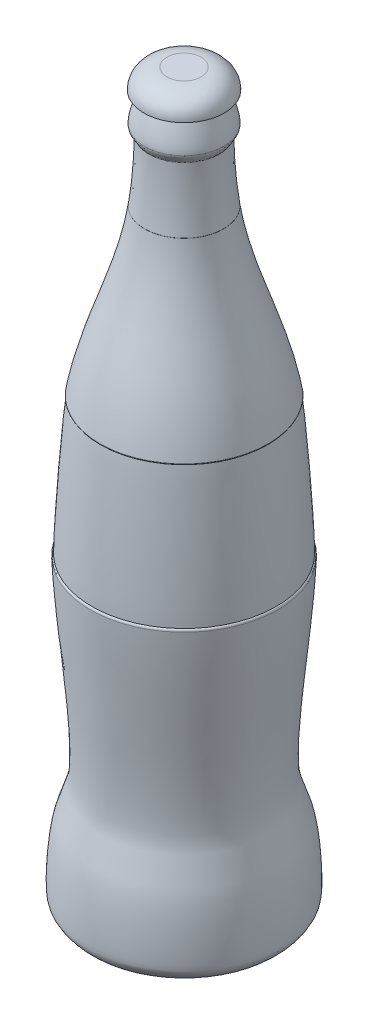
SolidWorks part; units mm, degrees
ref_plane "Plano frontal" through (0, 0, 0) normal (0, 0, 1) x (1, 0, 0)
ref_plane "Plano superior" through (0, 0, 0) normal (0, 1, 0) x (1, 0, 0)
ref_plane "Plano direito" through (0, 0, 0) normal (1, 0, 0) x (0, 0, -1)
sketch "Esboço1" plane through (0, 0, 0) normal (0, 0, 1) x (1, 0, 0)
  line L0 (46.2661, 215.0263) -> (246.2661, 215.0263) construction
  line L1 (103.0084, 498.8129) -> (276.3418, 498.8129) construction
sketch "Esboço2" plane through (0, 0, 0) normal (0, 0, 1) x (1, 0, 0)
  line L0 (0, 0) -> (0, 80) construction
  line L1 (-10, 80) -> (10, 80)
  line L2 (-10, 80) -> (-10, 0)
  line L3 (-10, 0) -> (10, 0)
  line L4 (10, 80) -> (10, 0)
  dimension "D1" = 20
  dimension "D2" = 80
sketch "Esboço3" plane through (0, 0, 0) normal (0, 0, 1) x (1, 0, 0)
  line L0 (69.3939, 0.7286) -> (71.7278, 0.7286) construction
  line L4 (66.4764, 70.3449) -> (66.4764, 74.4591) construction
  line L5 (61.2461, 48.1703) -> (61.269, 48.2958) construction
  line L6 (60.1212, 25.3308) -> (60.1272, 25.7681) construction
  line L7 (65.9996, 73.3703) -> (70.2369, 73.3703) construction
  line L9 (65.9493, 76.4714) -> (70.2369, 76.4714) construction
  line L10 (66.4764, 71.6551) -> (66.4764, 72.6387) construction
  line L11 (65.9996, 72.8706) -> (65.9996, 73.87) construction
  line L12 (65.9996, 74.64) -> (65.9996, 72.0995) construction
  line L13 (69.3157, 78.5883) -> (71.3057, 78.5883) construction
  line L14 (65.9493, 75.8068) -> (65.9493, 77.0589) construction
  line L15 (68.4095, 78.5883) -> (70.2369, 78.5883)
  line L16 (79.7348, 41.0622) -> (60.7391, 41.0622) construction
  line L18 (70.2369, 41.0622) -> (70.2369, -7.8367) construction
  line L20 (65.9493, 76.4714) -> (66.8395, 76.4714)
  line L22 (61.7174, 0.7286) -> (70.2369, 0.7286)
  line L23 (70.2369, 0.7286) -> (70.2369, 78.5883)
  spline S0 degree 3 poles (61.7174, 0.7286) (60.7515, 0.7286) (60.1104, 1.6271) (59.7378, 2.4704) (59.8897, 8.9407) (61.5165, 11.995) (61.7969, 19.0444) (60.545, 26.3685) (60.2321, 33.379) knots 0 0 0 0 0.208169 0.249428 0.412588 0.515444 0.574185 1 1 1 1
  spline S1 degree 3 poles (60.3714, 33.6283) (60.2694, 33.5907) (60.2337, 33.494) (60.2321, 33.379) knots 0 0 0 0 1 1 1 1
  spline S2 degree 3 poles (61.334, 48.0957) (61.0043, 45.4968) (60.4212, 37.1033) (60.3714, 33.6283) knots 0 0 0 0 1 1 1 1
  spline S3 degree 3 poles (66.4764, 72.402) (66.4764, 69.9707) (66.159, 65.6838) (64.1595, 57.2535) (62.2478, 53.6712) (61.2572, 48.2314) knots 0 0 0 0 0.259253 0.359253 1 1 1 1
  spline S4 degree 3 poles (61.2572, 48.2314) (61.2491, 48.1865) (61.2847, 48.1222) (61.334, 48.0957) knots 0 0 0 0 1 1 1 1
  spline S5 degree 3 poles (65.9996, 73.3703) (65.9996, 73.0591) (66.4764, 72.5293) (66.4764, 72.402) knots 0 0 0 0 1 1 1 1
  spline S6 degree 2 poles (65.9996, 73.3703) (65.9996, 74.1971) (66.8395, 76.4714) knots 0 0 0 1 1 1
  spline S7 degree 3 poles (68.4095, 78.5883) (67.1553, 78.5883) (65.9493, 77.852) (65.9493, 76.4714) knots 0 0 0 0 1 1 1 1
revolve "Revolução4" add sketch "Esboço3" angle 360 about L23
sketch "Esboço4" plane through (0, 0.7286, 0) normal (0, -1, 0) x (1, 0, 0)
  circle A0 centre (70.2369, 0) radius 0.5
  dimension "D1" = 1
extrude "Corte-extrusão3" cut sketch "Esboço4" against normal blind 0.4
ref_plane "Plano1" through (0, 65.7286, 0) normal (0, -1, 0) x (-1, 0, 0)
sketch "Esboço5" plane through (0, 65.7286, 0) normal (0, -1, 0) x (-1, 0, 0)
  circle A2 centre (-70.2369, 0) radius 12.162
extrude "Corte-extrusão4" cut sketch "Esboço5" against normal blind 0.01
